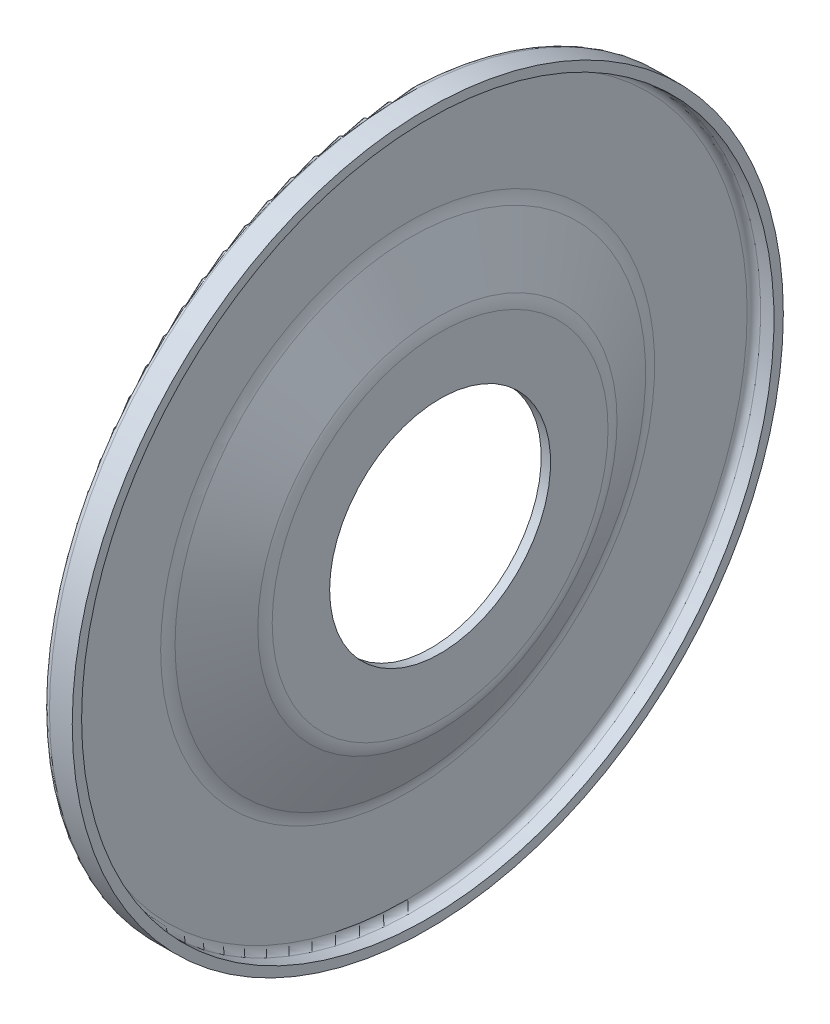
SolidWorks part; units mm, degrees
ref_plane "Alzado" through (0, 0, 0) normal (0, 0, 1) x (1, 0, 0)
ref_plane "Planta" through (0, 0, 0) normal (0, 1, 0) x (1, 0, 0)
ref_plane "Vista lateral" through (0, 0, 0) normal (1, 0, 0) x (0, 0, -1)
sketch "Croquis1" plane through (0, 0, 0) normal (0, 0, 1) x (1, 0, 0)
  line L0 (0, 0) -> (106.203, 0) construction
  line L1 (22.043, 8.25) -> (22.043, 12.5397)
  line L2 (21.8418, 13.414) -> (19.8211, 17.5712)
  line L3 (19.6199, 18.4455) -> (19.6199, 25.3511)
  line L4 (20.1199, 25.8511) -> (21.1226, 25.8511)
  line L5 (21.343, 8.25) -> (21.343, 12.3786)
  line L6 (21.1418, 13.2529) -> (19.1211, 17.4101)
  line L7 (18.9199, 18.2844) -> (18.9199, 26.0511)
  line L8 (19.4199, 26.5511) -> (21.1226, 26.5511)
  line L9 (21.1226, 25.8511) -> (21.1226, 26.5511)
  line L11 (21.343, 8.25) -> (22.043, 8.25)
  line L12 (22.043, 7.9681) -> (22.043, 13) construction
  line L13 (21.343, 7.9681) -> (21.343, 12.8389) construction
  line L14 (22.043, 13) -> (19.6199, 17.9852) construction
  line L15 (19.6199, 17.9852) -> (19.6199, 25.8511) construction
  line L16 (21.343, 12.8389) -> (18.9199, 17.8241) construction
  line L17 (18.9199, 17.8241) -> (18.9199, 26.5511) construction
  line L18 (18.9199, 26.5511) -> (21.1226, 26.5511) construction
  line L19 (19.6199, 25.8511) -> (21.1226, 25.8511) construction
  arc A0 (19.8211, 17.5712) -> (19.6199, 18.4455) centre (21.6199, 18.4455) cw
  arc A1 (19.1211, 17.4101) -> (18.9199, 18.2844) centre (20.9199, 18.2844) cw
  arc A2 (22.043, 12.5397) -> (21.8418, 13.414) centre (20.043, 12.5397) ccw
  arc A3 (18.9199, 26.0511) -> (19.4199, 26.5511) centre (19.4199, 26.0511) cw
  arc A4 (19.6199, 25.3511) -> (20.1199, 25.8511) centre (20.1199, 25.3511) cw
  arc A5 (21.343, 12.3786) -> (21.1418, 13.2529) centre (19.343, 12.3786) ccw
  dimension "D8" = 2
  dimension "D5" = 0.5
  dimension "D9" = 2
  dimension "D2" = 25.8511
  dimension "D3" = 154.078
  dimension "D4" = 2.2027
  dimension "D6" = 16.5
  dimension "D7" = 3.1231
  dimension "D10" = 12.3786
  dimension "D1" = 0.7
revolve "Revolución1" add sketch "Croquis1" angle 360 about L0
